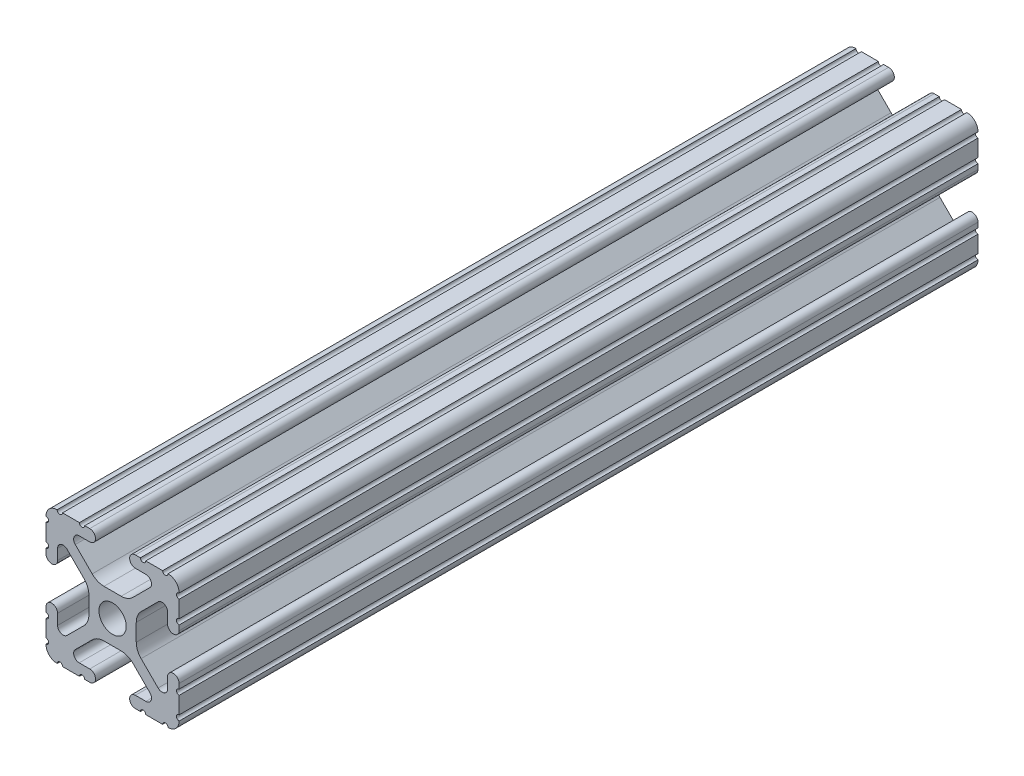
SolidWorks part; units mm, degrees
material "6105-T5 Aluminum"
ref_plane "Front Plane" through (0, 0, 0) normal (0, 0, 1) x (1, 0, 0)
ref_plane "Top Plane" through (0, 0, 0) normal (0, 1, 0) x (1, 0, 0)
ref_plane "Right Plane" through (0, 0, 0) normal (1, 0, 0) x (0, 0, -1)
sketch "Sketch1" plane through (0, 0, 0) normal (0, 0, 1) x (1, 0, 0)
  line L0 (10.5918, 12.7) -> (10.5664, 12.7)
  line L1 (9.5504, 12.7) -> (6.3246, 12.7)
  line L2 (5.3086, 12.7) -> (4.3561, 12.7)
  line L3 (4.3561, 10.4902) -> (6.3701, 10.4902)
  line L4 (7.1192, 8.6817) -> (3.8846, 5.4471)
  line L5 (1.6396, 4.5172) -> (-1.6396, 4.5172)
  line L6 (-3.8846, 5.4471) -> (-7.1192, 8.6817)
  line L7 (-6.3701, 10.4902) -> (-4.3561, 10.4902)
  line L8 (-4.3561, 12.7) -> (-5.3086, 12.7)
  line L9 (-6.3246, 12.7) -> (-9.5504, 12.7)
  line L10 (-10.5664, 12.7) -> (-10.5918, 12.7)
  line L11 (-12.7, 10.5918) -> (-12.7, 10.5664)
  line L12 (-12.7, 9.5504) -> (-12.7, 6.3246)
  line L13 (-12.7, 5.3086) -> (-12.7, 4.3561)
  line L14 (-10.4902, 4.3561) -> (-10.4902, 6.3701)
  line L15 (-8.6817, 7.1192) -> (-5.4471, 3.8846)
  line L16 (-4.5172, 1.6396) -> (-4.5172, -1.6396)
  line L17 (-5.4471, -3.8846) -> (-8.6817, -7.1192)
  line L18 (-10.4902, -6.3701) -> (-10.4902, -4.3561)
  line L19 (-12.7, -4.3561) -> (-12.7, -5.3086)
  line L20 (-12.7, -6.3246) -> (-12.7, -9.5504)
  line L21 (-12.7, -10.5664) -> (-12.7, -10.5918)
  line L22 (-10.5918, -12.7) -> (-10.5664, -12.7)
  line L23 (-9.5504, -12.7) -> (-6.3246, -12.7)
  line L24 (-5.3086, -12.7) -> (-4.3561, -12.7)
  line L25 (-4.3561, -10.4902) -> (-6.3701, -10.4902)
  line L26 (-7.1192, -8.6817) -> (-3.8846, -5.4471)
  line L27 (-1.6396, -4.5172) -> (1.6396, -4.5172)
  line L28 (3.8846, -5.4471) -> (7.1192, -8.6817)
  line L29 (6.3701, -10.4902) -> (4.3561, -10.4902)
  line L30 (4.3561, -12.7) -> (5.3086, -12.7)
  line L31 (6.3246, -12.7) -> (9.5504, -12.7)
  line L32 (10.5664, -12.7) -> (10.5918, -12.7)
  line L33 (12.7, -10.5918) -> (12.7, -10.5664)
  line L34 (12.7, -9.5504) -> (12.7, -6.3246)
  line L35 (12.7, -5.3086) -> (12.7, -4.3561)
  line L36 (10.4902, -4.3561) -> (10.4902, -6.3701)
  line L37 (8.6817, -7.1192) -> (5.4471, -3.8846)
  line L38 (4.5172, -1.6396) -> (4.5172, 1.6396)
  line L39 (5.4471, 3.8846) -> (8.6817, 7.1192)
  line L40 (10.4902, 6.3701) -> (10.4902, 4.3561)
  line L41 (12.7, 4.3561) -> (12.7, 5.3086)
  line L42 (12.7, 6.3246) -> (12.7, 9.5504)
  line L43 (12.7, 10.5664) -> (12.7, 10.5918)
  circle A0 centre (0, 0) radius 2.6035
  arc A1 (12.7, 10.5918) -> (10.5918, 12.7) centre (10.5918, 10.5918) ccw
  arc A2 (9.5504, 12.7) -> (10.5664, 12.7) centre (10.0584, 12.7) ccw
  arc A3 (5.3086, 12.7) -> (6.3246, 12.7) centre (5.8166, 12.7) ccw
  arc A4 (4.3561, 12.7) -> (4.3561, 10.4902) centre (4.3561, 11.5951) ccw
  arc A5 (7.1192, 8.6817) -> (6.3701, 10.4902) centre (6.3701, 9.4308) ccw
  arc A6 (1.6396, 4.5172) -> (3.8846, 5.4471) centre (1.6396, 7.6922) ccw
  arc A7 (-3.8846, 5.4471) -> (-1.6396, 4.5172) centre (-1.6396, 7.6922) ccw
  arc A8 (-6.3701, 10.4902) -> (-7.1192, 8.6817) centre (-6.3701, 9.4308) ccw
  arc A9 (-4.3561, 10.4902) -> (-4.3561, 12.7) centre (-4.3561, 11.5951) ccw
  arc A10 (-6.3246, 12.7) -> (-5.3086, 12.7) centre (-5.8166, 12.7) ccw
  arc A11 (-10.5664, 12.7) -> (-9.5504, 12.7) centre (-10.0584, 12.7) ccw
  arc A12 (-10.5918, 12.7) -> (-12.7, 10.5918) centre (-10.5918, 10.5918) ccw
  arc A13 (-12.7, 9.5504) -> (-12.7, 10.5664) centre (-12.7, 10.0584) ccw
  arc A14 (-12.7, 5.3086) -> (-12.7, 6.3246) centre (-12.7, 5.8166) ccw
  arc A15 (-12.7, 4.3561) -> (-10.4902, 4.3561) centre (-11.5951, 4.3561) ccw
  arc A16 (-8.6817, 7.1192) -> (-10.4902, 6.3701) centre (-9.4308, 6.3701) ccw
  arc A17 (-4.5172, 1.6396) -> (-5.4471, 3.8846) centre (-7.6922, 1.6396) ccw
  arc A18 (-5.4471, -3.8846) -> (-4.5172, -1.6396) centre (-7.6922, -1.6396) ccw
  arc A19 (-10.4902, -6.3701) -> (-8.6817, -7.1192) centre (-9.4308, -6.3701) ccw
  arc A20 (-10.4902, -4.3561) -> (-12.7, -4.3561) centre (-11.5951, -4.3561) ccw
  arc A21 (-12.7, -6.3246) -> (-12.7, -5.3086) centre (-12.7, -5.8166) ccw
  arc A22 (-12.7, -10.5664) -> (-12.7, -9.5504) centre (-12.7, -10.0584) ccw
  arc A23 (-12.7, -10.5918) -> (-10.5918, -12.7) centre (-10.5918, -10.5918) ccw
  arc A24 (-9.5504, -12.7) -> (-10.5664, -12.7) centre (-10.0584, -12.7) ccw
  arc A25 (-5.3086, -12.7) -> (-6.3246, -12.7) centre (-5.8166, -12.7) ccw
  arc A26 (-4.3561, -12.7) -> (-4.3561, -10.4902) centre (-4.3561, -11.5951) ccw
  arc A27 (-7.1192, -8.6817) -> (-6.3701, -10.4902) centre (-6.3701, -9.4308) ccw
  arc A28 (-1.6396, -4.5172) -> (-3.8846, -5.4471) centre (-1.6396, -7.6922) ccw
  arc A29 (3.8846, -5.4471) -> (1.6396, -4.5172) centre (1.6396, -7.6922) ccw
  arc A30 (6.3701, -10.4902) -> (7.1192, -8.6817) centre (6.3701, -9.4308) ccw
  arc A31 (4.3561, -10.4902) -> (4.3561, -12.7) centre (4.3561, -11.5951) ccw
  arc A32 (6.3246, -12.7) -> (5.3086, -12.7) centre (5.8166, -12.7) ccw
  arc A33 (10.5664, -12.7) -> (9.5504, -12.7) centre (10.0584, -12.7) ccw
  arc A34 (10.5918, -12.7) -> (12.7, -10.5918) centre (10.5918, -10.5918) ccw
  arc A35 (12.7, -9.5504) -> (12.7, -10.5664) centre (12.7, -10.0584) ccw
  arc A36 (12.7, -5.3086) -> (12.7, -6.3246) centre (12.7, -5.8166) ccw
  arc A37 (12.7, -4.3561) -> (10.4902, -4.3561) centre (11.5951, -4.3561) ccw
  arc A38 (8.6817, -7.1192) -> (10.4902, -6.3701) centre (9.4308, -6.3701) ccw
  arc A39 (4.5172, -1.6396) -> (5.4471, -3.8846) centre (7.6922, -1.6396) ccw
  arc A40 (5.4471, 3.8846) -> (4.5172, 1.6396) centre (7.6922, 1.6396) ccw
  arc A41 (10.4902, 6.3701) -> (8.6817, 7.1192) centre (9.4308, 6.3701) ccw
  arc A42 (10.4902, 4.3561) -> (12.7, 4.3561) centre (11.5951, 4.3561) ccw
  arc A43 (12.7, 6.3246) -> (12.7, 5.3086) centre (12.7, 5.8166) ccw
  arc A44 (12.7, 10.5664) -> (12.7, 9.5504) centre (12.7, 10.0584) ccw
extrude "Extrude1" add sketch "Sketch1" against normal blind 152.4
